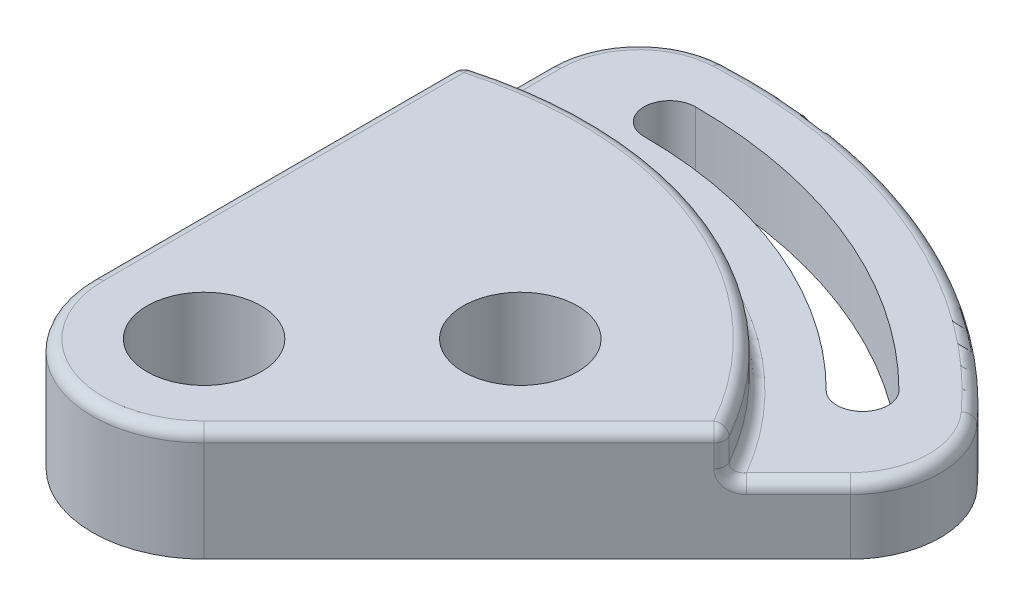
SolidWorks part; units mm, degrees
ref_plane "Front Plane" through (0, 0, 0) normal (0, 0, 1) x (1, 0, 0)
ref_plane "Top Plane" through (0, 0, 0) normal (0, 1, 0) x (1, 0, 0)
ref_plane "Right Plane" through (0, 0, 0) normal (1, 0, 0) x (0, 0, -1)
sketch "Sketch1" plane through (0, 0, 0) normal (0, 1, 0) x (1, 0, 0)
  line L0 (-5, 0) -> (-5, 23.9577)
  line L2 (3.5355, -3.5355) -> (20.4762, 13.4051)
  line L7 (0, 0) -> (9.3658, 22.611) construction
  line L8 (0, 20.8239) -> (14.7247, 14.7247) construction
  circle A0 centre (0, 0) radius 2.555
  arc A1 (3.5355, -3.5355) -> (-5, 0) centre (0, 0) cw
  arc A3 (0, 21.9739) -> (0, 19.6739) centre (0, 20.8239) ccw
  arc A4 (0, 21.9739) -> (15.5379, 15.5379) centre (0, 0) cw
  arc A5 (15.5379, 15.5379) -> (13.9116, 13.9116) centre (14.7247, 14.7247) cw
  arc A6 (13.9116, 13.9116) -> (0, 19.6739) centre (0, 0) ccw
  arc A7 (-5, 23.9577) -> (20.4762, 13.4051) centre (0, 0) cw
  circle A8 centre (7.0711, 7.0711) radius 2.555
  point P9 (0, 0)
  point P13 (6.9757, 7.1652)
  point P22 (9.3658, 22.611)
  point P23 (7.3624, 17.7743)
  dimension "D1" = 5.11
  dimension "D3" = 5
  dimension "D8" = 2.5
  dimension "D10" = 1.15
  dimension "D12" = 5
  dimension "D6" = 5.11
  dimension "D5" = 10
  dimension "D2" = 45
  dimension "D4" = 5
  dimension "D7" = 10
extrude "Boss-Extrude1" add sketch "Sketch1" along normal blind 5
fillet "Fillet1" radius 4 2 edges at (-5, 2.5, -23.9577) (20.4762, 2.5, -13.4051)
sketch "Sketch2" plane through (0, 5, 0) normal (0, 1, 0) x (1, 0, 0)
  line L0 (-5, 20.4495) -> (-5, 0) construction
  line L1 (3.5355, -3.5355) -> (17.9955, 10.9244) construction
  arc A0 (15.5379, 13.9116) -> (-1.15, 20.8239) centre (0, 0) ccw construction
  arc A1 (18.2336, 16.3251) -> (-1.3495, 24.4367) centre (0, 0) ccw
  arc A2 (12.8422, 11.498) -> (-0.9505, 17.2112) centre (0, 0) ccw
  arc A3 (12.8422, 11.498) -> (18.2336, 16.3251) centre (15.5379, 13.9116) ccw
  arc A4 (-1.3495, 24.4367) -> (-0.9505, 17.2112) centre (-1.15, 20.8239) ccw
  arc A5 (18.1303, 16.4398) -> (-1.1954, 24.4447) centre (0, 0) ccw construction
  arc A6 (13.9116, 13.9116) -> (15.5379, 15.5379) centre (14.7247, 14.7247) ccw construction
  arc A7 (0, 21.9739) -> (0, 19.6739) centre (0, 20.8239) ccw construction
  arc A8 (-0.9505, 17.2112) -> (-5, 16.4963) centre (0, 0) ccw
  arc A9 (12.8422, 11.498) -> (15.2002, 8.1291) centre (0, 0) cw
  point P5 (7.9811, 19.2681)
  point P10 (0, 0)
  arc M6 (18.1303, 16.4398) -> (-1.1954, 24.4447) centre (0, 0) ccw
  arc M7 (-1.1954, 24.4447) -> (-5, 20.4495) centre (-1, 20.4495) ccw
  line M8 (-5, 20.4495) -> (-5, 0)
  line M10 (3.5355, -3.5355) -> (17.9955, 10.9244)
  arc M11 (17.9955, 10.9244) -> (18.1303, 16.4398) centre (15.1671, 13.7529) ccw
  arc M12 (0, 21.9739) -> (15.5379, 15.5379) centre (0, 0) cw
  arc M13 (15.5379, 15.5379) -> (13.9116, 13.9116) centre (14.7247, 14.7247) cw
  arc M14 (13.9116, 13.9116) -> (0, 19.6739) centre (0, 0) ccw
  arc M15 (0, 19.6739) -> (0, 21.9739) centre (0, 20.8239) cw
extrude "Cut-Extrude1" cut sketch "Sketch2" against normal blind 2 contours A3 A9 M10 M11 | A4 A2 A3 M7 M11 M6 M15 M12 M13 M14 | A8 A4 M7 M8
fillet "Fillet3" radius 0.5 12 edges at (-5, 4, -16.4963) (-5, 3, -18.4729) (-3.8967, 3, -23.208) (9.3658, 3, -22.611) (19.1659, 3, -13.6551) (16.5978, 3, -9.5268) (-5, 5, -8.2481) (-1.9134, 5, 4.6194) (6.5965, 5, -15.9253) (6.5965, 3, -15.9253) (15.2002, 4, -8.1291) (9.3679, 5, -2.2968)
